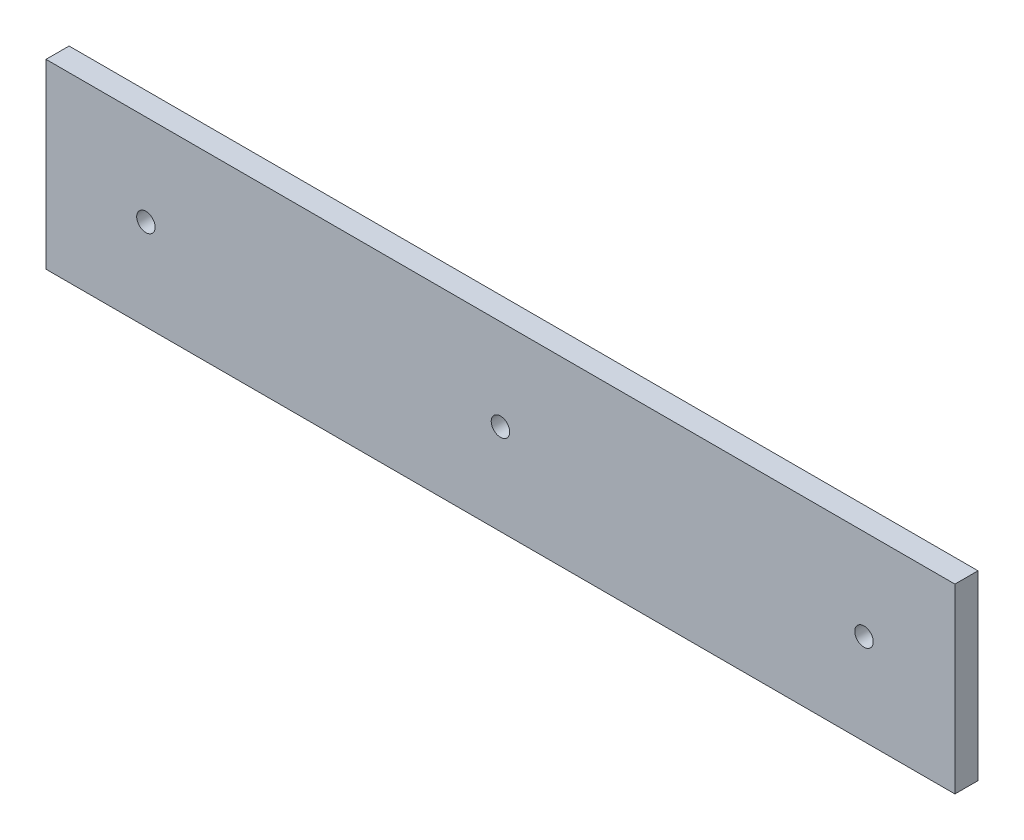
SolidWorks part; units mm, degrees
ref_plane "Front Plane" through (0, 0, 0) normal (0, 0, 1) x (1, 0, 0)
ref_plane "Top Plane" through (0, 0, 0) normal (0, 1, 0) x (1, 0, 0)
ref_plane "Right Plane" through (0, 0, 0) normal (1, 0, 0) x (0, 0, -1)
sketch "Sketch2" plane through (0, 0, 0) normal (0, 0, 1) x (1, 0, 0)
  line L0 (48.215, -9.4807) -> (48.215, 72.5613) construction
  line L1 (-51.785, 72.5613) -> (48.215, 72.5613)
  line L2 (-51.785, 72.5613) -> (-51.785, 52.5613)
  line L3 (-51.785, 52.5613) -> (48.215, 52.5613)
  line L4 (48.215, 72.5613) -> (48.215, 52.5613)
  circle A4 centre (-40.7925, 62.5613) radius 1.016
  circle A5 centre (-1.785, 62.5613) radius 1.016
  circle A6 centre (38.215, 62.5613) radius 1.016
extrude "Boss-Extrude1" add sketch "Sketch2" along normal blind 2.54
